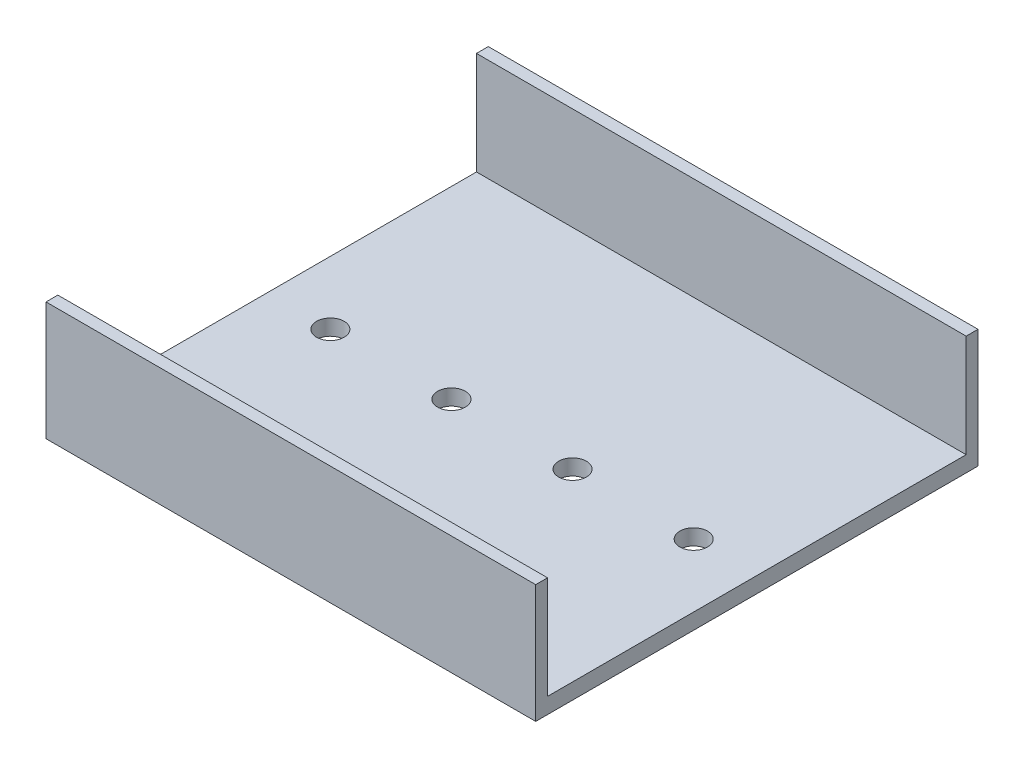
SolidWorks part; units mm, degrees
ref_plane "Front Plane" through (0, 0, 0) normal (0, 0, 1) x (1, 0, 0)
ref_plane "Top Plane" through (0, 0, 0) normal (0, 1, 0) x (1, 0, 0)
ref_plane "Right Plane" through (0, 0, 0) normal (1, 0, 0) x (0, 0, -1)
sketch "Sketch2" plane through (0, 0, 0) normal (0, 1, 0) x (1, 0, 0)
  line L1 (0, 0) -> (62, 0)
  line L2 (0, 0) -> (0, 56)
  line L3 (0, 56) -> (62, 56)
  line L4 (62, 0) -> (62, 56)
  dimension "D1" = 62
  dimension "D2" = 56
extrude "Boss-Extrude1" add sketch "Sketch2" along normal blind 15
sketch "Sketch3" plane through (0, 15, 0) normal (0, 1, 0) x (1, 0, 0)
  line L0 (0, 56) -> (0, 0) construction
  line L1 (0, 54.5) -> (62, 54.5)
  line L2 (0, 54.5) -> (0, 1.5)
  line L3 (0, 1.5) -> (62, 1.5)
  line L4 (62, 54.5) -> (62, 1.5)
  line L5 (62, 0) -> (62, 56) construction
  line L6 (0, 0) -> (62, 0) construction
  line L7 (62, 56) -> (0, 56) construction
  dimension "D1" = 1.5
  dimension "D2" = 1.5
extrude "Cut-Extrude1" cut sketch "Sketch3" against normal offset from surface (13 mm away) 2 up to face at (31, 0, -28)
sketch "Sketch4" plane through (0, 2, 0) normal (0, 1, 0) x (1, 0, 0)
  line L0 (0, 54.5) -> (0, 1.5) construction
  line L2 (62, 1.5) -> (62, 54.5) construction
  line L3 (8, 28) -> (23.3333, 28) construction
  line L4 (23.3333, 28) -> (38.6667, 28) construction
  line L5 (38.6667, 28) -> (54, 28) construction
  line L6 (8, 28) -> (0, 28) construction
  circle A0 centre (8, 28) radius 1.75
  circle A1 centre (23.3333, 28) radius 1.75
  circle A2 centre (38.6667, 28) radius 1.75
  circle A3 centre (54, 28) radius 1.75
  dimension "D1" = 8
  dimension "D2" = 3.5
  dimension "D3" = 8
extrude "Cut-Extrude2" cut sketch "Sketch4" against normal through all
